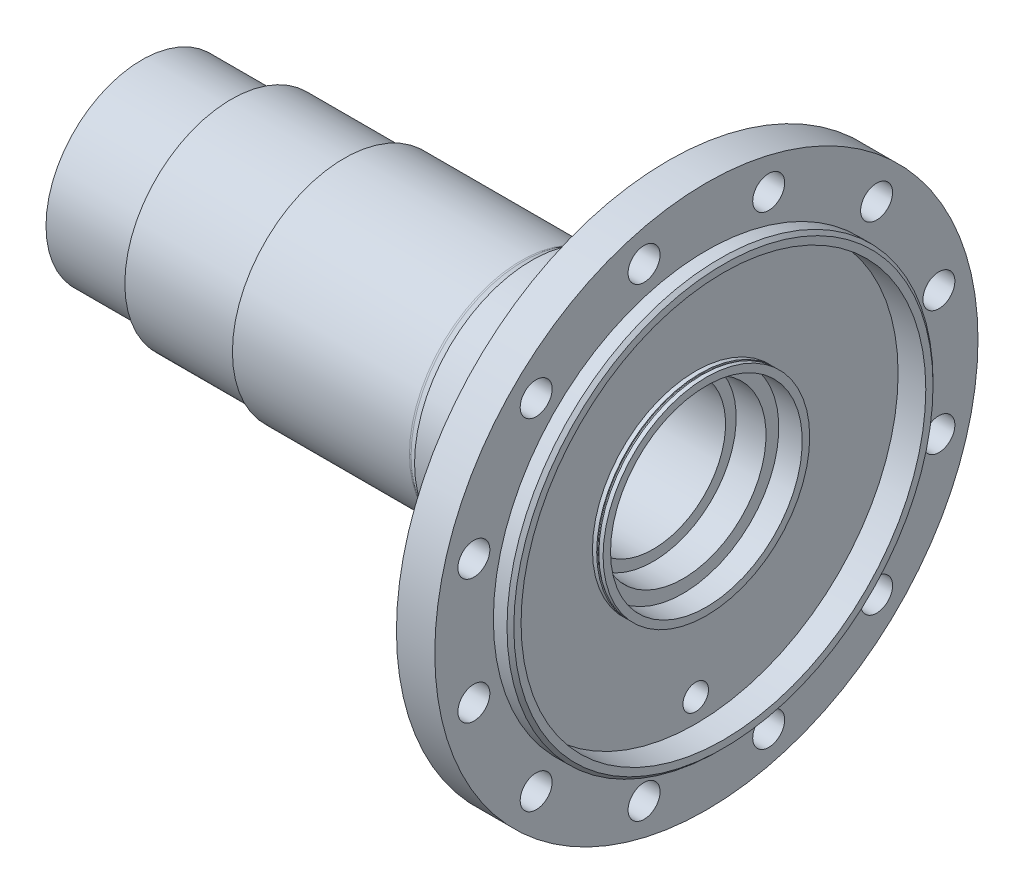
SolidWorks part; units mm, degrees
ref_plane "Спереди" through (0, 0, 0) normal (0, 0, 1) x (1, 0, 0)
ref_plane "Сверху" through (0, 0, 0) normal (0, 1, 0) x (1, 0, 0)
ref_plane "Справа" through (0, 0, 0) normal (1, 0, 0) x (0, 0, -1)
sketch "Эскиз1" plane through (0, 0, 0) normal (0, 0, 1) x (1, 0, 0)
  line L0 (0, 0) -> (273, 0)
  line L1 (0, 0) -> (0, 45)
  line L2 (0, 45) -> (42, 45)
  line L3 (42, 45) -> (42, 50)
  line L4 (42, 50) -> (95, 50)
  line L5 (95, 50) -> (95, 52.5)
  line L6 (95, 52.5) -> (178.134, 52.5)
  line L7 (179.134, 52.7679) -> (183, 55)
  line L8 (183, 55) -> (213, 55)
  line L9 (215, 57) -> (215, 60.7679)
  line L10 (215, 60.7679) -> (218, 62.5)
  line L11 (218, 62.5) -> (237, 62.5)
  line L12 (239, 64.5) -> (239, 65.5)
  line L13 (239, 65.5) -> (240.4142, 66.9142)
  line L14 (241, 68.3284) -> (241, 78)
  line L15 (241, 78) -> (244.4142, 81.4142)
  line L16 (245, 82.8284) -> (245, 92)
  line L17 (245, 92) -> (246.4142, 93.4142)
  line L18 (247, 94.8284) -> (247, 127.5)
  line L19 (247, 127.5) -> (265, 127.5)
  line L20 (265, 127.5) -> (265, 100)
  line L21 (265, 100) -> (271.4, 100)
  line L22 (271.4, 100) -> (273, 98.4)
  line L23 (273, 98.4) -> (273, 0)
  arc A0 (178.134, 52.5) -> (179.134, 52.7679) centre (178.134, 54.5) ccw
  arc A1 (213, 55) -> (215, 57) centre (213, 57) ccw
  arc A2 (237, 62.5) -> (239, 64.5) centre (237, 64.5) ccw
  arc A3 (240.4142, 66.9142) -> (241, 68.3284) centre (239, 68.3284) ccw
  arc A4 (244.4142, 81.4142) -> (245, 82.8284) centre (243, 82.8284) ccw
  arc A5 (246.4142, 93.4142) -> (247, 94.8284) centre (245, 94.8284) ccw
revolve "Повернуть1" add sketch "Эскиз1" angle 360 about L0
sketch "Эскиз2" plane through (0, 0, 0) normal (0, 0, 1) x (1, 0, 0)
  line L0 (0, 0) -> (273, 0)
  line L1 (0, 0) -> (0, 31)
  line L2 (0, 31) -> (203.5, 31)
  line L3 (203.5, 31) -> (203.5, 34)
  line L4 (203.5, 34) -> (240, 34)
  line L5 (240, 34) -> (240, 39)
  line L6 (240, 39) -> (254, 39)
  line L7 (254, 39) -> (254, 45)
  line L8 (254, 45) -> (265, 45)
  line L9 (265, 45) -> (265, 95)
  line L10 (265, 95) -> (273, 95)
  line L11 (273, 95) -> (273, 0)
revolve "Вырез-Повернуть1" cut sketch "Эскиз2" angle 360 about L0
sketch "Эскиз3" plane through (0, 0, 0) normal (0, 0, 1) x (1, 0, 0)
  line L0 (0, 0) -> (273, 0) construction
  line L1 (260, 48.5) -> (262, 48.5)
  line L2 (262, 48.5) -> (262, 95)
  line L3 (262, 95) -> (260, 95)
  line L4 (260, 95) -> (260, 48.5)
revolve "Rear_recess_left" cut sketch "Эскиз3" angle 360 about L0
sketch "Эскиз4" plane through (0, 0, 0) normal (0, 0, 1) x (1, 0, 0)
  line L0 (0, 0) -> (273, 0) construction
  line L1 (263, 48) -> (263, 95)
  line L2 (263, 95) -> (262, 95)
  line L3 (262, 95) -> (262, 48)
  arc A0 (262, 48) -> (262.5, 47.5) centre (262.5, 48) ccw
  arc A1 (262.5, 47.5) -> (263, 48) centre (262.5, 48) ccw
revolve "Collar_groove_nominal" cut sketch "Эскиз4" angle 360 about L0
sketch "Эскиз5" plane through (0, 0, 0) normal (0, 0, 1) x (1, 0, 0)
  line L0 (0, 0) -> (273, 0) construction
  line L1 (263, 48.5) -> (265, 48.5)
  line L2 (265, 48.5) -> (265, 95)
  line L3 (265, 95) -> (263, 95)
  line L4 (263, 95) -> (263, 48.5)
revolve "Rear_recess_lip" cut sketch "Эскиз5" angle 360 about L0
sketch "Эскиз6" plane through (0, 0, 0) normal (1, 0, 0) x (0, 0, -1)
  circle A0 centre (109.1496, 29.2466) radius 7.5
extrude "Вырез-Вытянуть1" cut sketch "Эскиз6" along normal through all
sketch "Эскиз7" plane through (0, 0, 0) normal (1, 0, 0) x (0, 0, -1)
  circle A0 centre (79.9031, 79.9031) radius 7.5
extrude "Вырез-Вытянуть2" cut sketch "Эскиз7" along normal through all
sketch "Эскиз8" plane through (0, 0, 0) normal (1, 0, 0) x (0, 0, -1)
  circle A0 centre (29.2466, 109.1496) radius 7.5
extrude "Вырез-Вытянуть3" cut sketch "Эскиз8" along normal through all
sketch "Эскиз9" plane through (0, 0, 0) normal (1, 0, 0) x (0, 0, -1)
  circle A0 centre (-29.2466, 109.1496) radius 7.5
extrude "Вырез-Вытянуть4" cut sketch "Эскиз9" along normal through all
sketch "Эскиз10" plane through (0, 0, 0) normal (1, 0, 0) x (0, 0, -1)
  circle A0 centre (-79.9031, 79.9031) radius 7.5
extrude "Вырез-Вытянуть5" cut sketch "Эскиз10" along normal through all
sketch "Эскиз11" plane through (0, 0, 0) normal (1, 0, 0) x (0, 0, -1)
  circle A0 centre (-109.1496, 29.2466) radius 7.5
extrude "Вырез-Вытянуть6" cut sketch "Эскиз11" along normal through all
sketch "Эскиз12" plane through (0, 0, 0) normal (1, 0, 0) x (0, 0, -1)
  circle A0 centre (-109.1496, -29.2466) radius 7.5
extrude "Вырез-Вытянуть7" cut sketch "Эскиз12" along normal through all
sketch "Эскиз13" plane through (0, 0, 0) normal (1, 0, 0) x (0, 0, -1)
  circle A0 centre (-79.9031, -79.9031) radius 7.5
extrude "Вырез-Вытянуть8" cut sketch "Эскиз13" along normal through all
sketch "Эскиз14" plane through (0, 0, 0) normal (1, 0, 0) x (0, 0, -1)
  circle A0 centre (-29.2466, -109.1496) radius 7.5
extrude "Вырез-Вытянуть9" cut sketch "Эскиз14" along normal through all
sketch "Эскиз15" plane through (0, 0, 0) normal (1, 0, 0) x (0, 0, -1)
  circle A0 centre (29.2466, -109.1496) radius 7.5
extrude "Вырез-Вытянуть10" cut sketch "Эскиз15" along normal through all
sketch "Эскиз16" plane through (0, 0, 0) normal (1, 0, 0) x (0, 0, -1)
  circle A0 centre (79.9031, -79.9031) radius 7.5
extrude "Вырез-Вытянуть11" cut sketch "Эскиз16" along normal through all
sketch "Эскиз17" plane through (0, 0, 0) normal (1, 0, 0) x (0, 0, -1)
  circle A0 centre (109.1496, -29.2466) radius 7.5
extrude "Вырез-Вытянуть12" cut sketch "Эскиз17" along normal through all
sketch "Эскиз18" plane through (0, 0, 0) normal (1, 0, 0) x (0, 0, -1)
  circle A0 centre (0, -84) radius 6
extrude "Вырез-Вытянуть13" cut sketch "Эскиз18" along normal through all
